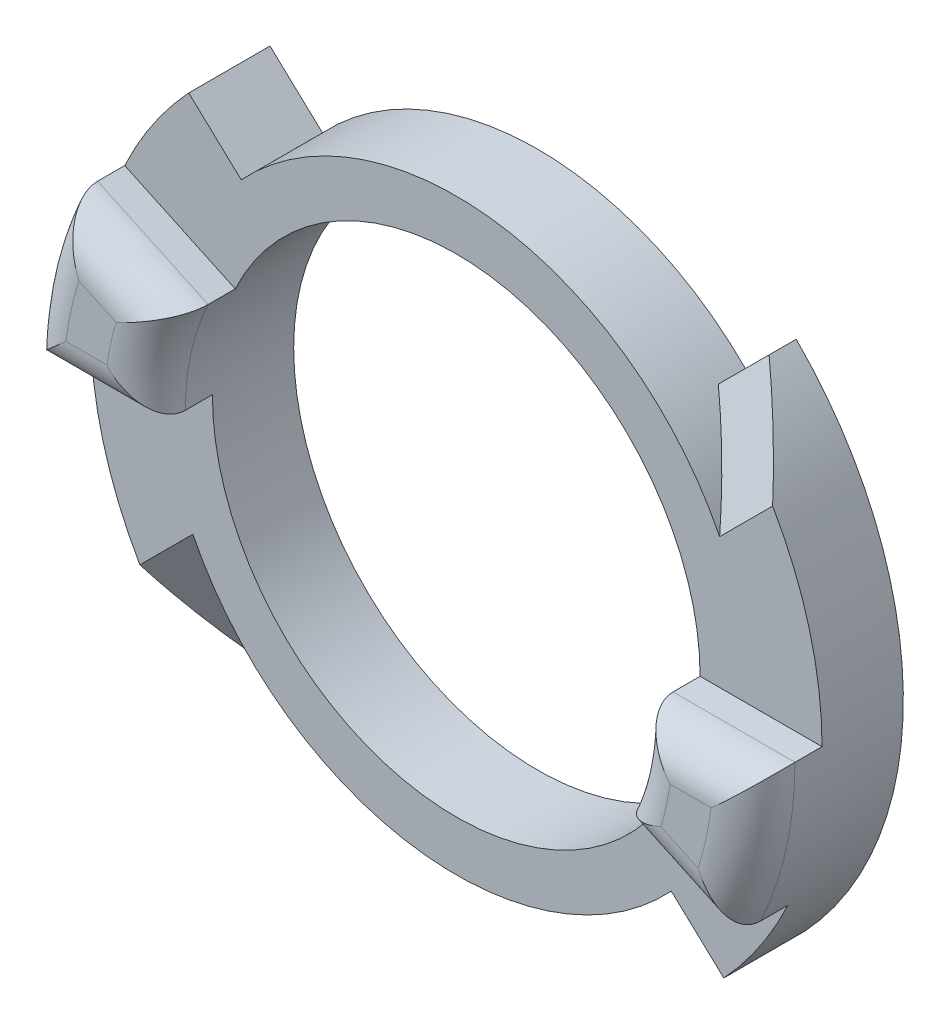
SolidWorks part; units mm, degrees
ref_plane "Front Plane" through (0, 0, 0) normal (0, 0, 1) x (1, 0, 0)
ref_plane "Top Plane" through (0, 0, 0) normal (0, 1, 0) x (1, 0, 0)
ref_plane "Right Plane" through (0, 0, 0) normal (1, 0, 0) x (0, 0, -1)
sketch "Sketch1" plane through (0, 0, 0) normal (0, 0, 1) x (1, 0, 0)
  line L0 (-23.5, 7.5) -> (-23.5, 21.25)
  line L1 (-23.5, 7.5) -> (-23.5, -6.25)
  line L2 (-23.5, 7.5) -> (-33.2227, -2.2227)
  line L3 (-23.5, 7.5) -> (-13.7773, 17.2227)
  line L4 (-23.5, 7.5) -> (-33.2227, 17.2227)
  line L5 (-23.5, 7.5) -> (-13.7773, -2.2227)
  circle A0 centre (-23.5, 7.5) radius 13.75
  circle A1 centre (-23.5, 7.5) radius 9
  circle A2 centre (-23.5, 7.5) radius 10.85
  dimension "D1" = 18
  dimension "D2" = 21.7
extrude "Boss-Extrude1" add sketch "Sketch1" along normal blind 3 contours A2 L4 A0 L2 | L4 A2 L2 A1 | L0 A2 L4 A1 | L3 A2 L0 A1 | L5 A2 L3 A1 | L1 A2 L5 A1 | L2 A2 L1 A1 | A2 L5 A0 L3
sketch "Sketch2" plane through (0, 0, 3) normal (0, 0, 1) x (1, 0, 0)
  line L0 (-23.5, 7.5) -> (-9.75, 7.5)
  line L1 (-23.5, 7.5) -> (-37.25, 7.5)
  line L2 (-15.8279, -0.1721) -> (-17.136, 1.136)
  line L3 (-23.5, 7.5) -> (-33.2227, 17.2227)
  line L6 (-15.8279, -0.1721) -> (-13.7773, -2.2227)
  line L7 (-13.7773, 17.2227) -> (-15.8279, 15.1721)
  line L8 (-31.1721, 15.1721) -> (-33.2227, 17.2227)
  line L9 (-33.2227, -2.2227) -> (-31.1721, -0.1721)
  line L10 (-15.8279, -0.1721) -> (-13.7773, -2.2227)
  line L11 (-13.7773, 17.2227) -> (-15.8279, 15.1721)
  line L12 (-31.1721, 15.1721) -> (-33.2227, 17.2227)
  line L13 (-33.2227, -2.2227) -> (-31.1721, -0.1721)
  arc A0 (-13.7773, -2.2227) -> (-13.7773, 17.2227) centre (-23.5, 7.5) ccw construction
  arc A1 (-33.2227, 17.2227) -> (-33.2227, -2.2227) centre (-23.5, 7.5) ccw construction
  circle A2 centre (-23.5, 7.5) radius 9
  arc A6 (-31.1721, -0.1721) -> (-15.8279, -0.1721) centre (-23.5, 7.5) ccw
  arc A7 (-13.7773, -2.2227) -> (-13.7773, 17.2227) centre (-23.5, 7.5) ccw
  arc A8 (-15.8279, 15.1721) -> (-31.1721, 15.1721) centre (-23.5, 7.5) ccw
  arc A9 (-33.2227, 17.2227) -> (-33.2227, -2.2227) centre (-23.5, 7.5) ccw
  arc A10 (-31.1721, -0.1721) -> (-15.8279, -0.1721) centre (-23.5, 7.5) ccw
  arc A11 (-13.7773, -2.2227) -> (-13.7773, 17.2227) centre (-23.5, 7.5) ccw
  arc A12 (-15.8279, 15.1721) -> (-31.1721, 15.1721) centre (-23.5, 7.5) ccw
  arc A13 (-33.2227, 17.2227) -> (-33.2227, -2.2227) centre (-23.5, 7.5) ccw
  line M11 (-15.8279, -0.1721) -> (-13.7773, -2.2227)
  arc M12 (-13.7773, -2.2227) -> (-13.7773, 17.2227) centre (-23.5, 7.5) ccw
  line M15 (-31.1721, 15.1721) -> (-33.2227, 17.2227)
  arc M16 (-33.2227, 17.2227) -> (-33.2227, -2.2227) centre (-23.5, 7.5) ccw
  circle M18 centre (-23.5, 7.5) radius 9
  dimension "D1" = 0
extrude "Boss-Extrude2" add sketch "Sketch2" along normal blind 2.5 contours L3 L1 M18 M15 M16 | L2 L0 M11 M12 M18
chamfer "Chamfer1" distance 2 angle 60 1 edges at (-32.1974, -1.1974, 3)
chamfer "Chamfer2" distance 2 angle 60 1 edges at (-14.8026, 16.1974, 3)
sketch "Sketch3" plane through (0, 0, 5.5) normal (0, 0, 1) x (1, 0, 0)
  line L0 (-23.5, 7.5) -> (-11.0383, 1.689)
  line L1 (-23.5, -3.65) -> (-23.5, -6.25) construction
  line L2 (-23.5, 7.5) -> (-35.9617, 13.311)
  line L5 (-29.864, 13.864) -> (-33.2227, 17.2227)
  line L6 (-37.25, 7.5) -> (-32.5, 7.5)
  line L7 (-29.864, 13.864) -> (-33.2227, 17.2227)
  line L8 (-37.25, 7.5) -> (-32.5, 7.5)
  line L9 (-17.136, 1.136) -> (-13.7773, -2.2227)
  line L10 (-9.75, 7.5) -> (-14.5, 7.5)
  line L11 (-17.136, 1.136) -> (-13.7773, -2.2227)
  line L12 (-9.75, 7.5) -> (-14.5, 7.5)
  arc A0 (-13.7773, -2.2227) -> (-9.75, 7.5) centre (-23.5, 7.5) ccw construction
  arc A3 (-29.864, 13.864) -> (-32.5, 7.5) centre (-23.5, 7.5) ccw
  arc A4 (-33.2227, 17.2227) -> (-37.25, 7.5) centre (-23.5, 7.5) ccw
  arc A5 (-29.864, 13.864) -> (-32.5, 7.5) centre (-23.5, 7.5) ccw
  arc A6 (-33.2227, 17.2227) -> (-37.25, 7.5) centre (-23.5, 7.5) ccw
  arc A7 (-13.7773, -2.2227) -> (-9.75, 7.5) centre (-23.5, 7.5) ccw
  arc A8 (-17.136, 1.136) -> (-14.5, 7.5) centre (-23.5, 7.5) ccw
  arc A9 (-13.7773, -2.2227) -> (-9.75, 7.5) centre (-23.5, 7.5) ccw
  arc A10 (-17.136, 1.136) -> (-14.5, 7.5) centre (-23.5, 7.5) ccw
  arc M11 (-32.5, 7.5) -> (-29.864, 13.864) centre (-23.5, 7.5) cw
  line M12 (-29.864, 13.864) -> (-33.2227, 17.2227)
  arc M13 (-33.2227, 17.2227) -> (-37.25, 7.5) centre (-23.5, 7.5) ccw
  dimension "D1" = 65
  dimension "D2" = 0
  dimension "D3" = 0
extrude "Cut-Extrude1" cut sketch "Sketch3" against normal blind 2.5 contours A10 L11 A9 L0 | L2 M11 M12 M13
sketch "Sketch4" plane through (0, 0, 3) normal (0, 0, 1) x (1, 0, 0)
  circle A0 centre (-23.5, 7.5) radius 13.5
  circle A1 centre (-23.5, 7.5) radius 17.223
  dimension "D1" = 27
extrude "Cut-Extrude2" cut sketch "Sketch4" against normal through all both and the other way through all
sketch "Sketch5" plane through (0, 0, 3) normal (0, 0, 1) x (1, 0, 0)
  line L0 (-23.5, 7.5) -> (-33.3733, 16.707)
  line L1 (-23.5, 18.65) -> (-23.5, 21.25) construction
  line L2 (-31.1721, 15.1721) -> (-23.5, 7.5)
  line L3 (-23.5, 7.5) -> (-13.6267, -1.707)
  line L4 (-23.5, 7.5) -> (-13.9541, -2.0459)
  line L6 (-14.5, 7.5) -> (-10, 7.5)
  line L7 (-11.8242, 14.2768) -> (-13.7799, 12.3211)
  line L8 (-31.1721, 15.1721) -> (-33.0459, 17.0459)
  line L9 (-35.7352, 13.2053) -> (-31.6568, 11.3036)
  line L10 (-14.5, 7.5) -> (-10, 7.5)
  line L11 (-11.8242, 14.2768) -> (-13.7799, 12.3211)
  line L12 (-31.1721, 15.1721) -> (-33.0459, 17.0459)
  line L13 (-35.7352, 13.2053) -> (-31.6568, 11.3036)
  arc A0 (-13.9541, -2.0459) -> (-11.2648, 1.7947) centre (-23.5, 7.5) ccw construction
  circle A1 centre (-23.5, 7.5) radius 10.85
  arc A4 (-10, 7.5) -> (-11.8242, 14.2768) centre (-23.5, 7.5) ccw
  arc A5 (-13.7799, 12.3211) -> (-31.1721, 15.1721) centre (-23.5, 7.5) ccw
  arc A6 (-33.0459, 17.0459) -> (-35.7352, 13.2053) centre (-23.5, 7.5) ccw
  arc A7 (-14.5, 7.5) -> (-31.6568, 11.3036) centre (-23.5, 7.5) ccw
  arc A8 (-10, 7.5) -> (-11.8242, 14.2768) centre (-23.5, 7.5) ccw
  arc A9 (-13.7799, 12.3211) -> (-31.1721, 15.1721) centre (-23.5, 7.5) ccw
  arc A10 (-33.0459, 17.0459) -> (-35.7352, 13.2053) centre (-23.5, 7.5) ccw
  arc A11 (-14.5, 7.5) -> (-31.6568, 11.3036) centre (-23.5, 7.5) ccw
  line M14 (-15.8279, -0.1721) -> (-13.9541, -2.0459)
  arc M15 (-13.9541, -2.0459) -> (-11.2648, 1.7947) centre (-23.5, 7.5) ccw
  dimension "D1" = 47
  dimension "D2" = 0
extrude "Cut-Extrude3" cut sketch "Sketch5" against normal through all both contours L12 A10 L0 A1 | A1 L3 M14 M15
fillet "Fillet1" radius 1.5 8 edges at (-36.68, 10.4219, 5.5) (-32.2867, 9.448, 5.5) (-34.75, 7.5, 5.5) (-33.696, 12.2545, 5.5) (-10.32, 4.5781, 5.5) (-14.7133, 5.552, 5.5) (-12.25, 7.5, 5.5) (-13.304, 2.7455, 5.5)
